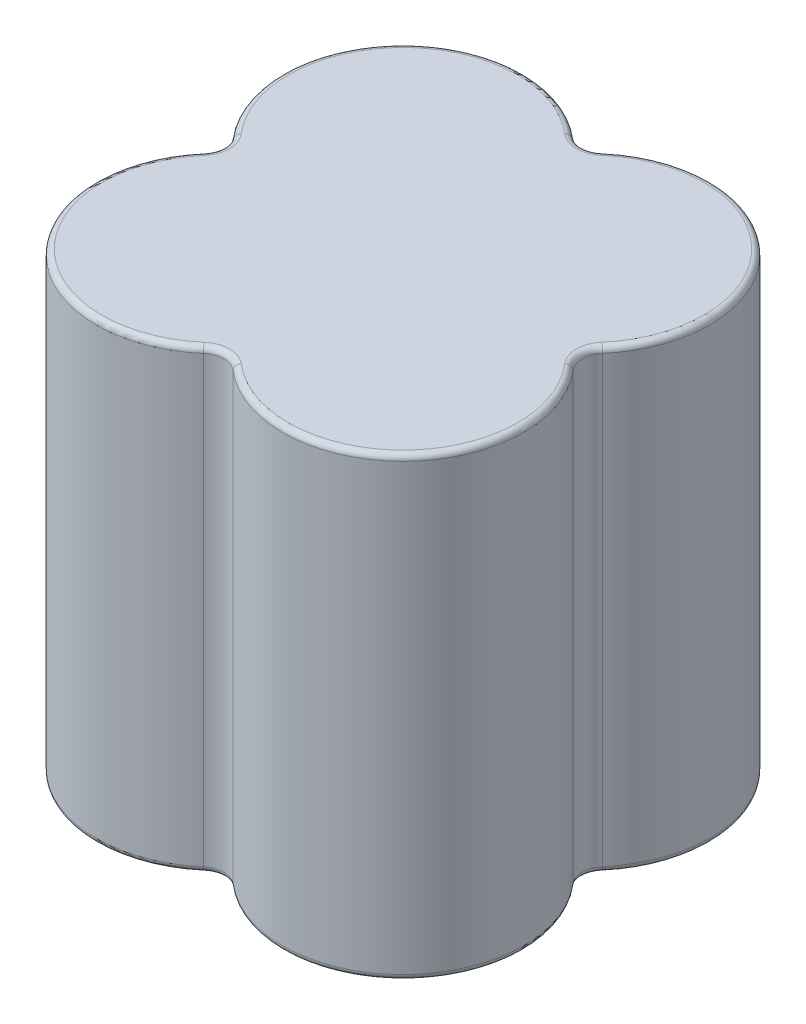
SolidWorks part; units mm, degrees
ref_plane "Front Plane" through (0, 0, 0) normal (1, 0, 0) x (0, 1, 0)
ref_plane "Top Plane" through (0, 0, 0) normal (0, 0, 1) x (0, 1, 0)
ref_plane "Right Plane" through (0, 0, 0) normal (0, 1, 0) x (-1, 0, 0)
sketch "Sketch1" plane through (0, 0, 0) normal (0, 1, 0) x (-1, 0, 0)
  arc A0 (-1.2973, -16.2039) -> (-16.2032, -1.3061) centre (-8.1778, -8.1822) cw
  arc A1 (-16.2032, -1.3061) -> (-16.2039, 1.2973) centre (-17.722, -0.0048) ccw
  arc A2 (-16.2039, 1.2973) -> (-1.3061, 16.2032) centre (-8.1822, 8.1778) cw
  arc A3 (-1.3061, 16.2032) -> (1.2973, 16.2039) centre (-0.0048, 17.722) ccw
  arc A4 (1.2973, 16.2039) -> (16.2032, 1.3061) centre (8.1778, 8.1822) cw
  arc A5 (16.2032, 1.3061) -> (16.2039, -1.2973) centre (17.722, 0.0048) ccw
  arc A6 (16.2039, -1.2973) -> (1.3061, -16.2032) centre (8.1822, -8.1778) cw
  arc A7 (1.3061, -16.2032) -> (-1.2973, -16.2039) centre (0.0048, -17.722) ccw
extrude "Boss-Extrude1" add sketch "Sketch1" along normal blind 40
fillet "Fillet1" radius 0.5 16 edges at (-0.0043, 0, -15.722) (-15.6572, 0, -15.6486) (-15.722, 0, 0.0043) (-15.6486, 0, 15.6572) (0.0043, 0, 15.722) (15.6572, 0, 15.6486) (15.722, 0, -0.0043) (15.6486, 0, -15.6572) (-0.0043, 40, -15.722) (-15.6572, 40, -15.6486) (-15.722, 40, 0.0043) (-15.6486, 40, 15.6572) (0.0043, 40, 15.722) (15.6572, 40, 15.6486) (15.722, 40, -0.0043) (15.6486, 40, -15.6572)
